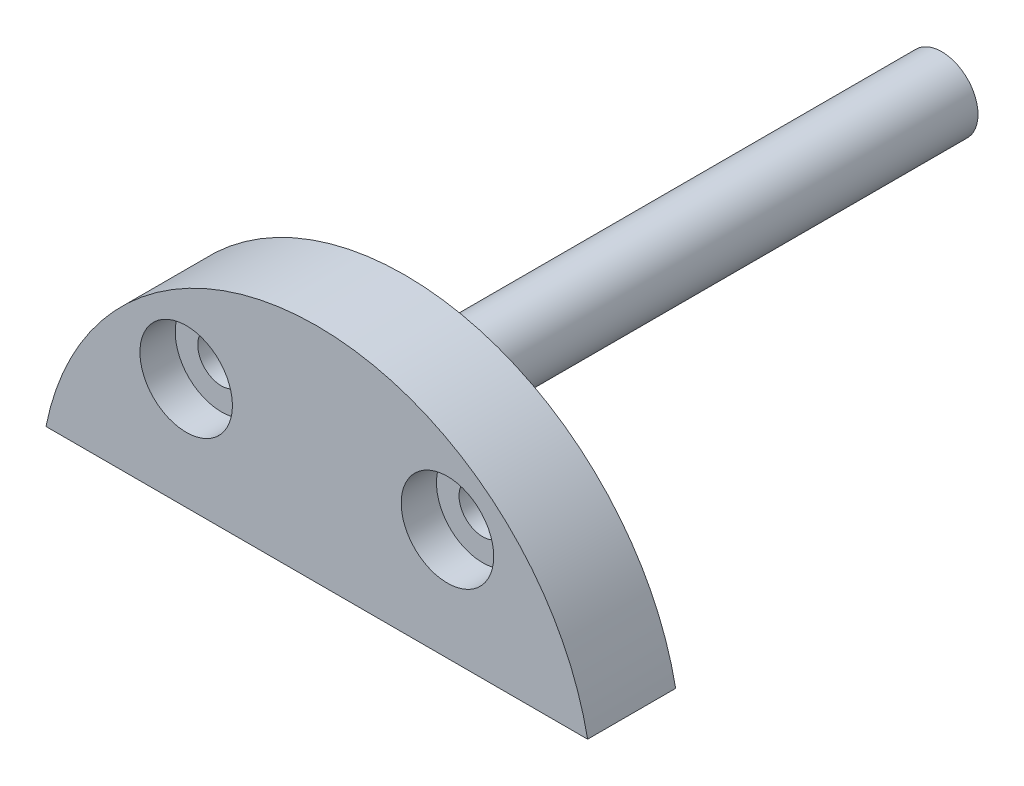
SolidWorks part; units mm, degrees
ref_plane "Alzado" through (0, 0, 0) normal (0, 0, 1) x (1, 0, 0)
ref_plane "Planta" through (0, 0, 0) normal (0, 1, 0) x (1, 0, 0)
ref_plane "Vista lateral" through (0, 0, 0) normal (1, 0, 0) x (0, 0, -1)
sketch "Croquis1" plane through (0, 0, 0) normal (0, 0, 1) x (1, 0, 0)
  line L0 (-29.715, 0) -> (29.715, 0)
  line L1 (0, 0) -> (0, 24.43) construction
  arc A0 (-29.715, 0) -> (29.715, 0) centre (0, -5.8567) cw
  dimension "D1" = 24.43
  dimension "D2" = 59.43
extrude "Saliente-Extruir1" add sketch "Croquis1" against normal blind 9.66
sketch "Croquis2" plane through (0, 0, -9.66) normal (0, 0, -1) x (-1, 0, 0)
  line L0 (0, 0) -> (0, 24.43) construction
  circle A0 centre (0, 12.215) radius 3.98
  dimension "D1" = 7.96
extrude "Saliente-Extruir2" add sketch "Croquis2" along normal blind 58.91
sketch "Croquis3" plane through (0, 0, 0) normal (0, 0, 1) x (1, 0, 0)
  circle A0 centre (-14.3341, 12.215) radius 2.6 construction
  circle A2 centre (14.3341, 12.215) radius 2.6 construction
  circle A5 centre (-14.3341, 12.215) radius 2.6
  circle A6 centre (14.3341, 12.215) radius 2.6
extrude "Cortar-Extruir1" cut sketch "Croquis3" against normal up to next
sketch "Croquis4" plane through (0, 0, 0) normal (0, 0, 1) x (1, 0, 0)
  circle A0 centre (14.3341, 12.215) radius 5.075
  circle A1 centre (-14.3341, 12.215) radius 5.075
  dimension "D1" = 10.15
extrude "Cortar-Extruir2" cut sketch "Croquis4" against normal blind 3.87
